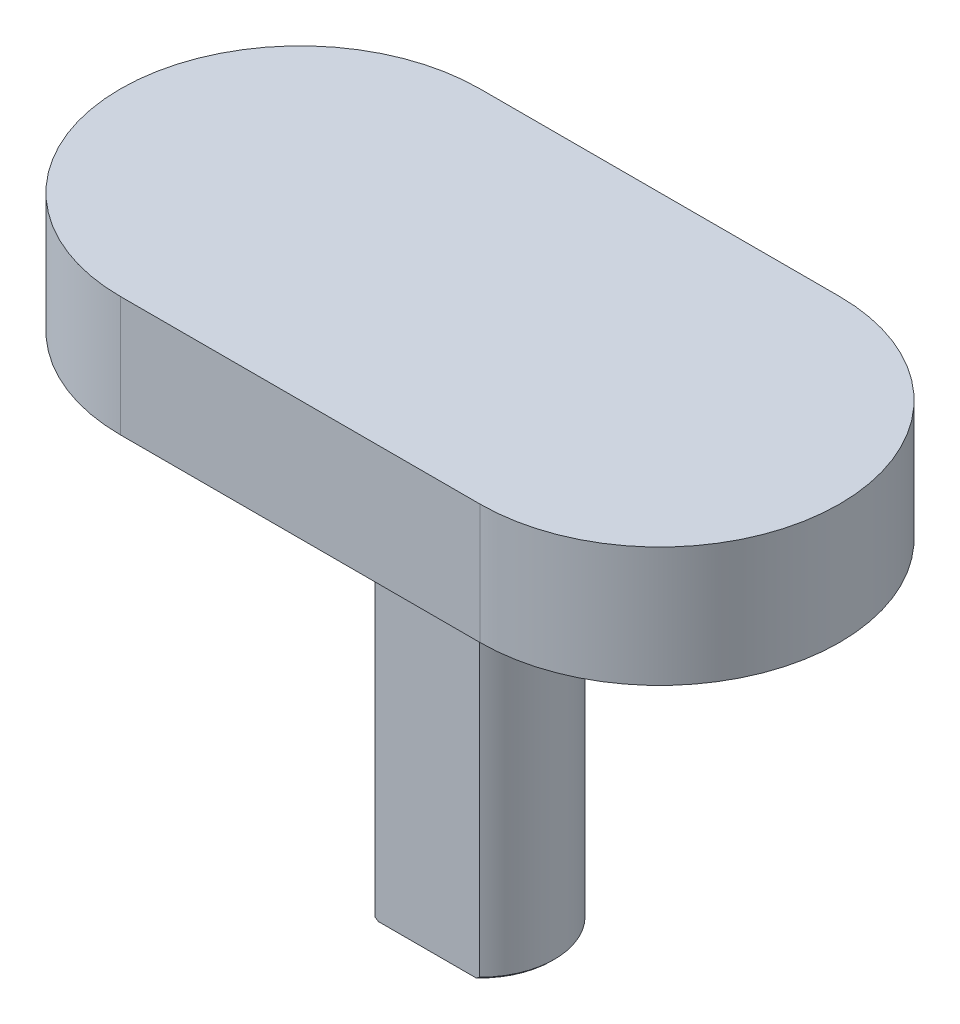
SolidWorks part; units mm, degrees
material "1.4021 (X20Cr13)"
ref_plane "前视基准面" through (0, 0, 0) normal (0, 0, 1) x (1, 0, 0)
ref_plane "上视基准面" through (0, 0, 0) normal (0, 1, 0) x (1, 0, 0)
ref_plane "右视基准面" through (0, 0, 0) normal (1, 0, 0) x (0, 0, -1)
sketch "草图1" plane through (0, 0, 0) normal (0, 1, 0) x (1, 0, 0)
  line L1 (-75, 75) -> (75, 75)
  line L3 (-75, -75) -> (75, -75)
  arc A0 (-75, 75) -> (-75, -75) centre (-75, 0) ccw
  arc A1 (75, -75) -> (75, 75) centre (75, 0) ccw
  point P0 (0, 0)
  dimension "D5" = 75
  dimension "D6" = 75
  dimension "D1" = 150
  dimension "D2" = 150
  dimension "D3" = 75
  dimension "D4" = 75
extrude "凸台-拉伸1" add sketch "草图1" along normal blind 50
sketch "草图2" plane through (0, 0, 0) normal (0, -1, 0) x (1, 0, 0)
  line L1 (-75, 65) -> (75, 65)
  line L3 (-75, -65) -> (75, -65)
  arc A0 (-75, 65) -> (-75, -65) centre (-75, 0) ccw
  arc A1 (75, -65) -> (75, 65) centre (75, 0) ccw
  point P0 (0, 0)
  dimension "D5" = 65
  dimension "D6" = 65
  dimension "D1" = 150
  dimension "D2" = 130
  dimension "D3" = 65
  dimension "D4" = 75
extrude "切除-拉伸1" cut sketch "草图2" against normal blind 40
sketch "草图4" plane through (0, 40, 0) normal (0, -1, 0) x (1, 0, 0)
  line L1 (-24.9199, 30) -> (24.9199, 30)
  line L3 (-24.9199, -30) -> (24.9199, -30)
  arc A0 (-24.9199, 30) -> (-24.9199, -30) centre (0, 0) ccw
  arc A1 (24.9199, -30) -> (24.9199, 30) centre (0, 0) ccw
  dimension "D1" = 39
  dimension "D2" = 30
  dimension "D3" = 30
extrude "凸台-拉伸2" add sketch "草图4" along normal blind 20
sketch "草图5" plane through (0, 20, 0) normal (0, -1, 0) x (1, 0, 0)
  line L1 (-21.8403, 22) -> (21.8403, 22)
  line L3 (-21.8403, -22) -> (21.8403, -22)
  arc A0 (-21.8403, 22) -> (-21.8403, -22) centre (0, 0) ccw
  arc A1 (21.8403, -22) -> (21.8403, 22) centre (0, 0) ccw
  dimension "D1" = 22
  dimension "D3" = 31
  dimension "D2" = 22
extrude "凸台-拉伸3" add sketch "草图5" along normal blind 195
sketch "草图6" plane through (0, -175, 0) normal (0, -1, 0) x (1, 0, 0)
  circle A0 centre (0, 0) radius 11
  dimension "D1" = 22
extrude "切除-拉伸2" cut sketch "草图6" against normal blind 15
ref_plane "基准面3" through (0, -160, 0) normal (0, 1, 0) x (1, 0, 0)
sketch "草图7" plane through (0, -160, 0) normal (0, 1, 0) x (1, 0, 0)
  circle A0 centre (0, 0) radius 18
  dimension "D1" = 36
extrude "切除-拉伸3" cut sketch "草图7" along normal blind 200
sketch "草图8" plane through (0, -175, 0) normal (0, -1, 0) x (1, 0, 0)
  line L0 (-48.0691, 0) -> (48.0691, 0) construction
  circle A0 centre (0, 0) radius 24.5 construction
  circle A1 centre (24.5, 0) radius 2.5
  circle A2 centre (17.3241, -17.3241) radius 2.5
  circle A4 centre (-17.3241, -17.3241) radius 2.5
  circle A5 centre (-24.5, 0) radius 2.5
  circle A6 centre (-17.3241, 17.3241) radius 2.5
  circle A8 centre (17.3241, 17.3241) radius 2.5
  circle A9 centre (0, -24.5) radius 2.5 [skipped]
  circle A10 centre (0, 24.5) radius 2.5 [skipped]
  circle A12 centre (-24.5, 0) radius 2.5
  circle A14 centre (0, 24.5) radius 2.5 [skipped]
  circle A15 centre (0, -24.5) radius 2.5 [skipped]
  point P5 (0, 0)
  dimension "D1" = 49
  dimension "D2" = 5
  dimension "D3" = 8
  dimension "D4" = 4
hole_wizard "M6 螺纹孔1" positions "草图9" profile "草图10" tap size "M6" standard "GB"
sketch "草图9" plane through (0, -175, 0) normal (0, -1, 0) x (-1, 0, 0)
  point P0 (24.5, 0)
  point P3 (17.3241, -17.3241)
  point P6 (-17.3241, -17.3241)
  point P9 (-24.5, 0)
  point P12 (-17.3241, 17.3241)
  point P15 (17.3241, 17.3241)
cosmetic thread "孔螺蚊线1" parameters "D1"=12, "D2"=6
cosmetic thread "孔螺蚊线2" parameters "D1"=12, "D2"=6
cosmetic thread "孔螺蚊线3" parameters "D1"=12, "D2"=6
cosmetic thread "孔螺蚊线4" parameters "D1"=12, "D2"=6
cosmetic thread "孔螺蚊线5" parameters "D1"=12, "D2"=6
cosmetic thread "孔螺蚊线6" parameters "D1"=12, "D2"=6
sketch "草图10" plane through (-24.5, -175, 0) normal (1, 0, 0) x (0, 0, -1)
  line L0 (0, 0) -> (0, 14.5022)
  line L1 (0, 14.5022) -> (2.5, 13)
  line L2 (2.5, 13) -> (2.5, 0)
  line L5 (2.5, 0) -> (0, 0)
  line L10 (0, 14.5022) -> (-2.5, 13) construction
  line L11 (0, -6.35) -> (0, 107.95) construction
  dimension "螺纹孔钻头直径" = 5
  dimension "螺纹孔钻头深度" = 13
  dimension "导头角度" = 118
chamfer "倒角1" distance 1 angle 45 2 edges at (31, -175, 0) (-31, -175, 0)
